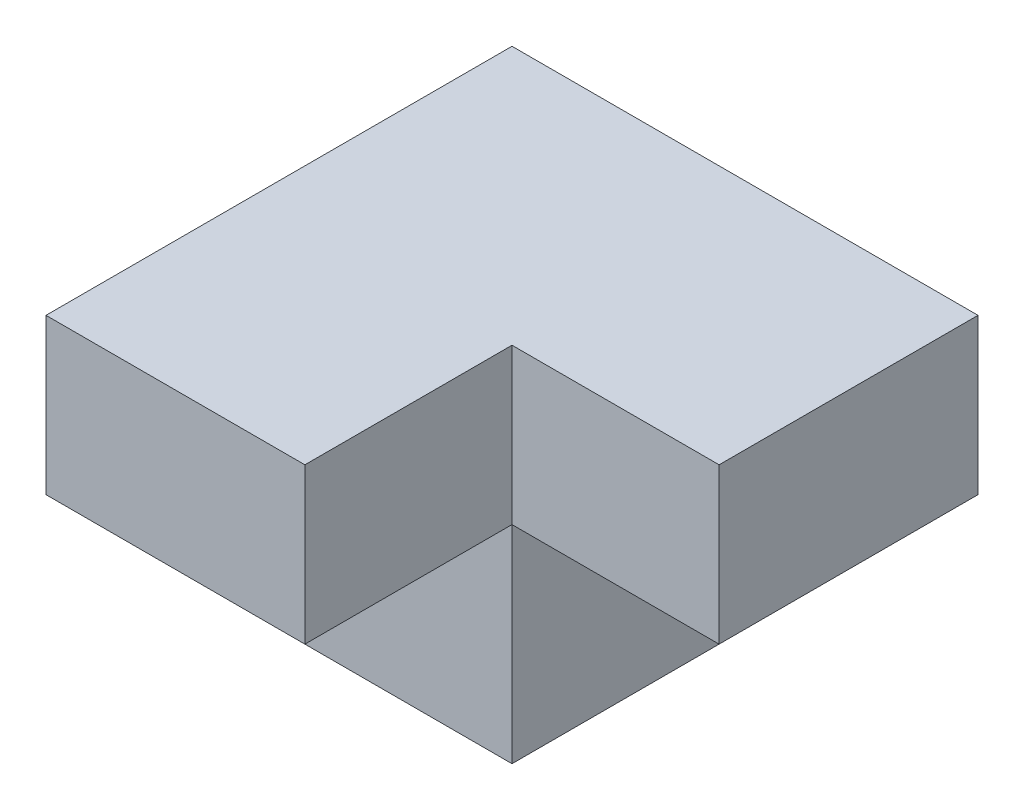
SolidWorks part; units mm, degrees
material "PLA"
ref_plane "Front Plane" through (0, 0, 0) normal (0, 0, 1) x (1, 0, 0)
ref_plane "Top Plane" through (0, 0, 0) normal (0, 1, 0) x (1, 0, 0)
ref_plane "Right Plane" through (0, 0, 0) normal (1, 0, 0) x (0, 0, -1)
sketch "Sketch3" plane through (0, 0, 0) normal (0, 1, 0) x (1, 0, 0)
  line L1 (12.5, 12.5) -> (-12.5, 12.5)
  line L2 (-12.5, 12.5) -> (-12.5, -12.5)
  line L3 (-12.5, -12.5) -> (12.5, -12.5)
  line L4 (12.5, -12.5) -> (12.5, 12.5)
  circle A0 centre (0, 0) radius 12.5 construction
  dimension "D1" = 25
extrude "Boss-Extrude1" add sketch "Sketch3" along normal blind 15 and the other way blind 20
sketch "Extrusion Profile" plane through (0, -20, 0) normal (0, -1, 0) x (-1, 0, 0)
  line L0 (4.4, -0.0029) -> (4.3971, 0)
  line L1 (4.3971, 0) -> (4.4, 0.0029)
  line L2 (3.9, -0.21) -> (3.69, 0) construction
  line L3 (3.9, -2.8393) -> (3.9, -0.21) construction
  line L4 (6.5607, -5.5) -> (3.9, -2.8393) construction
  line L5 (8.2, -5.5) -> (6.5607, -5.5) construction
  line L6 (8.2, -3.125) -> (8.2, -5.5) construction
  line L7 (8.545, -3.125) -> (8.2, -3.125) construction
  line L8 (10, -4.58) -> (8.545, -3.125) construction
  line L9 (10, -9.5) -> (10, -4.58) construction
  line L10 (4.58, -10) -> (9.5, -10) construction
  line L11 (3.125, -8.545) -> (4.58, -10) construction
  line L12 (3.125, -8.2) -> (3.125, -8.545) construction
  line L13 (5.5, -8.2) -> (3.125, -8.2) construction
  line L14 (5.5, -6.5607) -> (5.5, -8.2) construction
  line L15 (2.8393, -3.9) -> (5.5, -6.5607) construction
  line L16 (0.21, -3.9) -> (2.8393, -3.9) construction
  line L17 (0, -3.69) -> (0.21, -3.9) construction
  line L18 (4.4, 0.0029) -> (4.4, 2.6322)
  line L19 (4.4, 2.6322) -> (6.7678, 5)
  line L20 (-0.21, -3.9) -> (0, -3.69) construction
  line L21 (-2.8393, -3.9) -> (-0.21, -3.9) construction
  line L22 (-5.5, -6.5607) -> (-2.8393, -3.9) construction
  line L23 (-5.5, -8.2) -> (-5.5, -6.5607) construction
  line L24 (-3.125, -8.2) -> (-5.5, -8.2) construction
  line L25 (-3.125, -8.545) -> (-3.125, -8.2) construction
  line L26 (-4.58, -10) -> (-3.125, -8.545) construction
  line L27 (-9.5, -10) -> (-4.58, -10) construction
  line L28 (-10, -4.58) -> (-10, -9.5) construction
  line L29 (-8.545, -3.125) -> (-10, -4.58) construction
  line L30 (-8.2, -3.125) -> (-8.545, -3.125) construction
  line L31 (-8.2, -5.5) -> (-8.2, -3.125) construction
  line L32 (-6.5607, -5.5) -> (-8.2, -5.5) construction
  line L33 (-3.9, -2.8393) -> (-6.5607, -5.5) construction
  line L34 (-3.9, -0.21) -> (-3.9, -2.8393) construction
  line L35 (-3.69, 0) -> (-3.9, -0.21) construction
  line L36 (6.7678, 5) -> (7.7, 5)
  line L37 (7.7, 5) -> (7.7, 2.625)
  line L38 (-3.9, 0.21) -> (-3.69, 0) construction
  line L39 (-3.9, 2.8393) -> (-3.9, 0.21) construction
  line L40 (-6.5607, 5.5) -> (-3.9, 2.8393) construction
  line L41 (-8.2, 5.5) -> (-6.5607, 5.5) construction
  line L42 (-8.2, 3.125) -> (-8.2, 5.5) construction
  line L43 (-8.545, 3.125) -> (-8.2, 3.125) construction
  line L44 (-10, 4.58) -> (-8.545, 3.125) construction
  line L45 (-10, 9.5) -> (-10, 4.58) construction
  line L46 (-4.58, 10) -> (-9.5, 10) construction
  line L47 (-3.125, 8.545) -> (-4.58, 10) construction
  line L48 (-3.125, 8.2) -> (-3.125, 8.545) construction
  line L49 (-5.5, 8.2) -> (-3.125, 8.2) construction
  line L50 (-5.5, 6.5607) -> (-5.5, 8.2) construction
  line L51 (-2.8393, 3.9) -> (-5.5, 6.5607) construction
  line L52 (-0.21, 3.9) -> (-2.8393, 3.9) construction
  line L53 (0, 3.69) -> (-0.21, 3.9) construction
  line L54 (7.7, 2.625) -> (8.7521, 2.625)
  line L55 (8.7521, 2.625) -> (10.5, 4.3729)
  line L56 (10.5, 4.3729) -> (10.5, 9.5)
  line L57 (9.5, 10.5) -> (4.3729, 10.5)
  line L58 (4.3729, 10.5) -> (2.625, 8.7521)
  line L59 (2.625, 8.7521) -> (2.625, 7.7)
  line L60 (2.625, 7.7) -> (5, 7.7)
  line L61 (5, 7.7) -> (5, 6.7678)
  line L62 (5, 6.7678) -> (2.6322, 4.4)
  line L63 (2.6322, 4.4) -> (0.0029, 4.4)
  line L64 (0.0029, 4.4) -> (0, 4.3971)
  line L65 (0, 4.3971) -> (-0.0029, 4.4)
  line L66 (-0.0029, 4.4) -> (-2.6322, 4.4)
  line L67 (-2.6322, 4.4) -> (-5, 6.7678)
  line L68 (-5, 6.7678) -> (-5, 7.7)
  line L69 (-5, 7.7) -> (-2.625, 7.7)
  line L70 (-2.625, 7.7) -> (-2.625, 8.7521)
  line L71 (-2.625, 8.7521) -> (-4.3729, 10.5)
  line L72 (-4.3729, 10.5) -> (-9.5, 10.5)
  line L73 (-10.5, 9.5) -> (-10.5, 4.3729)
  line L74 (-10.5, 4.3729) -> (-8.7521, 2.625)
  line L75 (-8.7521, 2.625) -> (-7.7, 2.625)
  line L76 (-7.7, 2.625) -> (-7.7, 5)
  line L77 (-7.7, 5) -> (-6.7678, 5)
  line L78 (-6.7678, 5) -> (-4.4, 2.6322)
  line L79 (-4.4, 2.6322) -> (-4.4, 0.0029)
  line L80 (-4.4, 0.0029) -> (-4.3971, 0)
  line L81 (-4.3971, 0) -> (-4.4, -0.0029)
  line L82 (-4.4, -0.0029) -> (-4.4, -2.6322)
  line L83 (-4.4, -2.6322) -> (-6.7678, -5)
  line L84 (-6.7678, -5) -> (-7.7, -5)
  line L85 (-7.7, -5) -> (-7.7, -2.625)
  line L86 (-7.7, -2.625) -> (-8.7521, -2.625)
  line L87 (-8.7521, -2.625) -> (-10.5, -4.3729)
  line L88 (-10.5, -4.3729) -> (-10.5, -9.5)
  line L89 (-9.5, -10.5) -> (-4.3729, -10.5)
  line L90 (-4.3729, -10.5) -> (-2.625, -8.7521)
  line L91 (-2.625, -8.7521) -> (-2.625, -7.7)
  line L92 (-2.625, -7.7) -> (-5, -7.7)
  line L93 (-5, -7.7) -> (-5, -6.7678)
  line L94 (-5, -6.7678) -> (-2.6322, -4.4)
  line L95 (-2.6322, -4.4) -> (-0.0029, -4.4)
  line L96 (-0.0029, -4.4) -> (0, -4.3971)
  line L97 (0, -4.3971) -> (0.0029, -4.4)
  line L98 (0.0029, -4.4) -> (2.6322, -4.4)
  line L99 (2.6322, -4.4) -> (5, -6.7678)
  line L100 (5, -6.7678) -> (5, -7.7)
  line L101 (5, -7.7) -> (2.625, -7.7)
  line L102 (2.625, -7.7) -> (2.625, -8.7521)
  line L103 (2.625, -8.7521) -> (4.3729, -10.5)
  line L104 (4.3729, -10.5) -> (9.5, -10.5)
  line L105 (10.5, -9.5) -> (10.5, -4.3729)
  line L106 (10.5, -4.3729) -> (8.7521, -2.625)
  line L107 (8.7521, -2.625) -> (7.7, -2.625)
  line L108 (7.7, -2.625) -> (7.7, -5)
  line L109 (7.7, -5) -> (6.7678, -5)
  line L110 (6.7678, -5) -> (4.4, -2.6322)
  line L111 (4.4, -2.6322) -> (4.4, -0.0029)
  line L176 (0.21, 3.9) -> (0, 3.69) construction
  line L177 (2.8393, 3.9) -> (0.21, 3.9) construction
  line L178 (5.5, 6.5607) -> (2.8393, 3.9) construction
  line L179 (5.5, 8.2) -> (5.5, 6.5607) construction
  line L180 (3.125, 8.2) -> (5.5, 8.2) construction
  line L181 (3.125, 8.545) -> (3.125, 8.2) construction
  line L182 (4.58, 10) -> (3.125, 8.545) construction
  line L183 (9.5, 10) -> (4.58, 10) construction
  line L184 (10, 4.58) -> (10, 9.5) construction
  line L185 (8.545, 3.125) -> (10, 4.58) construction
  line L186 (8.2, 3.125) -> (8.545, 3.125) construction
  line L187 (8.2, 5.5) -> (8.2, 3.125) construction
  line L188 (6.5607, 5.5) -> (8.2, 5.5) construction
  line L189 (3.9, 2.8393) -> (6.5607, 5.5) construction
  line L190 (3.9, 0.21) -> (3.9, 2.8393) construction
  line L191 (3.69, 0) -> (3.9, 0.21) construction
  arc A0 (9.5, -10) -> (10, -9.5) centre (9.5, -9.5) ccw construction
  arc A1 (-10, -9.5) -> (-9.5, -10) centre (-9.5, -9.5) ccw construction
  arc A2 (-9.5, 10) -> (-10, 9.5) centre (-9.5, 9.5) ccw construction
  arc A3 (10.5, 9.5) -> (9.5, 10.5) centre (9.5, 9.5) ccw
  arc A4 (-9.5, 10.5) -> (-10.5, 9.5) centre (-9.5, 9.5) ccw
  arc A5 (-10.5, -9.5) -> (-9.5, -10.5) centre (-9.5, -9.5) ccw
  arc A6 (9.5, -10.5) -> (10.5, -9.5) centre (9.5, -9.5) ccw
  arc A11 (10, 9.5) -> (9.5, 10) centre (9.5, 9.5) ccw construction
  point P2 (0, 0)
  point P7 (0, 0)
  point P27 (0, 0)
  point P47 (0, 0)
  point P84 (0, 0)
  dimension "D1" = 4
  dimension "D2" = 0.5
extrude "Cut-Extrude1" cut sketch "Extrusion Profile" against normal offset from surface (30 mm away) 5 up to face at (0, 15, 0)
sketch "Sketch5" plane through (0, 0, 12.5) normal (0, 0, 1) x (1, 0, 0)
  line L0 (12.5, -20) -> (12.5, 15) construction
  line L1 (-12.5, 15) -> (12.5, 15)
  line L2 (-12.5, 15) -> (-12.5, 0)
  line L3 (-12.5, 0) -> (12.5, 0)
  line L4 (12.5, 15) -> (12.5, 0)
  dimension "D1" = 15
extrude "Boss-Extrude2" add sketch "Sketch5" along normal blind 20
sketch "Sketch6" plane through (12.5, 0, 0) normal (1, 0, 0) x (0, 0, -1)
  line L0 (-12.5, 15) -> (12.5, 15)
  line L1 (-12.5, 15) -> (-12.5, 0)
  line L2 (-12.5, 0) -> (12.5, 0)
  line L3 (12.5, 15) -> (12.5, 0)
extrude "Boss-Extrude3" add sketch "Sketch6" along normal blind 20
